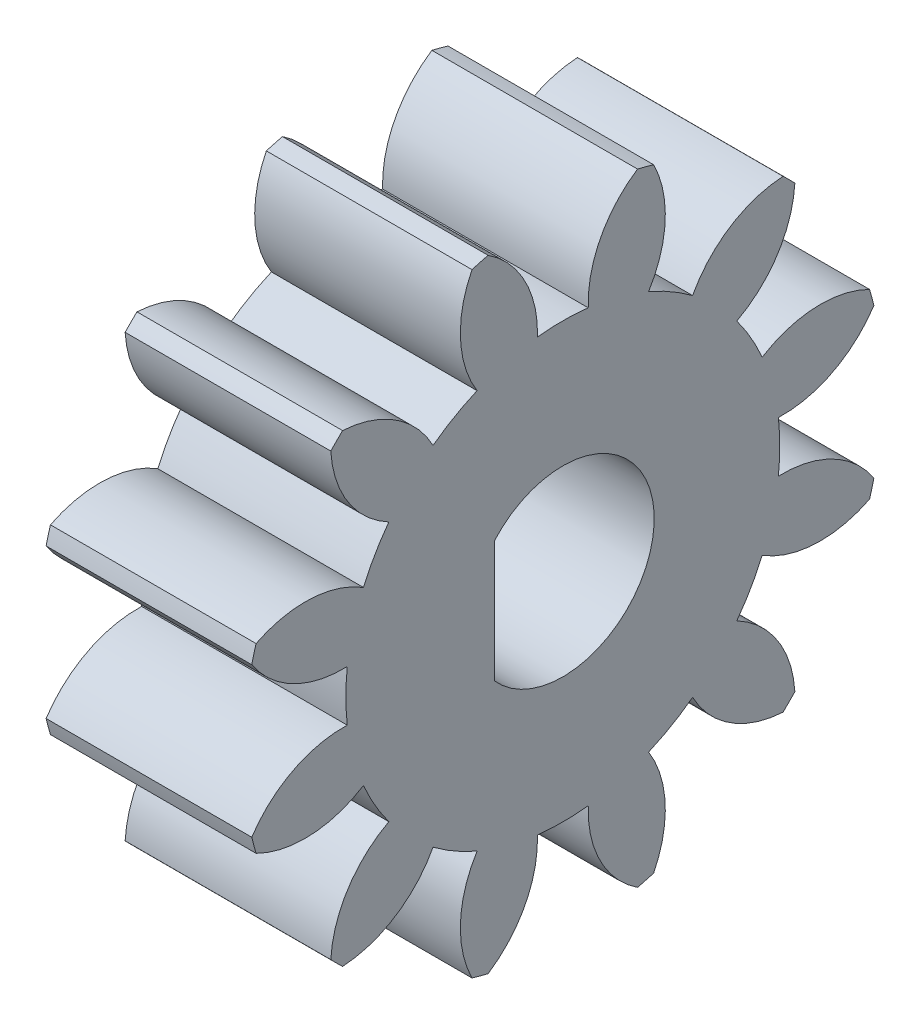
SolidWorks part; units mm, degrees
ref_plane "Plane1" through (0, 0, 0) normal (0, 0, 1) x (1, 0, 0)
ref_plane "Plane2" through (0, 0, 0) normal (0, 1, 0) x (1, 0, 0)
ref_plane "Plane3" through (0, 0, 0) normal (1, 0, 0) x (0, 0, -1)
sketch "HoldingSke" plane through (0, 0, 0) normal (0, 1, 0) x (1, 0, 0)
  line L0 (0, 0) -> (0.4891, -0.104)
  line L1 (-15, 0) -> (100, 0) construction
  line L2 (0, 0) -> (-2.1039, 2.3779)
  line L3 (0, 0) -> (-11.863, 4.5341)
  line L4 (0, 0) -> (8.4473, 1.7955)
  line L5 (0, 0) -> (-46.8476, -17.4728)
  line L6 (0, 0) -> (-7.4607, -5.0337)
  line L7 (-2.1039, 2.3779) -> (8.6586, 51.2059)
  line L8 (-76.2, 54.61) -> (-74.8, 54.61)
  line L9 (-71.009, 38.7566) -> (-53.1078, 45.2721)
  line L10 (-76.2, 71.12) -> (104.1128, 71.12)
  line L11 (0, 0) -> (-9, 0)
  line L12 (-76.2, 101.6) -> (-76.133, 101.6)
  line L13 (24.9733, 27.94) -> (52.9518, 28.4284)
  line L14 (24.9733, 27.94) -> (24.9743, 27.94)
  line L15 (24.9733, 27.94) -> (100.4006, 29.5858)
  line L16 (-63.627, -2) -> (-12.827, -2)
  circle A0 centre (0, 0) radius 4
  circle A1 centre (0, 0) radius 9.499
  circle A2 centre (0, 0) radius 37.5
  circle A3 centre (0, 0) radius 4
  dimension "MHD" = 18.998
  dimension "Hub_dia" = 75
  dimension "Bore" = 8
  dimension "MBD" = 8
  dimension "Num_teeth" = 12
  dimension "Pitch" = 0.5
  dimension "Overall_len" = 50
  dimension "Show_teeth" = 12
  dimension "Thickness" = 9
  dimension "OAL" = 50.0001
  dimension "T_dim" = 1.4
  dimension "Ap" = 20
  dimension "H" = 19.05
  dimension "Pitch_radius" = 180.3128
  dimension "Width" = 9
  dimension "Backlash" = 0.067
  dimension "Addendum_fac" = 1
  dimension "Dedendum_fac" = 1.25
  dimension "Clearance_fac" = 0.25
  dimension "Dedendum_add" = 0.001
  dimension "Module" = 2
sketch "BasProSke" plane through (0, 0, 0) normal (0, 1, 0) x (1, 0, 0)
  line L0 (-10, 0) -> (60, 0) construction
  line L1 (0, 0) -> (0, 14)
  line L2 (0, 0) -> (9, 0)
  line L3 (9, 0) -> (9, 14)
  line L4 (9, 14) -> (0, 14)
  dimension "Thickness" = 9
  dimension "Diameter" = 28
revolve "Base-Revolve" add sketch "BasProSke" angle 360 about L0
sketch "TooCutSke" plane through (0, 0, 0) normal (1, 0, 0) x (0, 0, -1)
  line L1 (0, 0) -> (0, 107) construction
  line L2 (0, 0) -> (-1.6834, 11.8813) construction
  line L3 (0, 0) -> (-6.1662, 23.0126) construction
  line L4 (-1.6834, 11.8813) -> (-3.0831, 11.5063) construction
  arc A0 (1.1119, 9.4337) -> (-1.1119, 9.4337) centre (0, 0) ccw
  arc A1 (3.2981, 13.6321) -> (-3.2981, 13.6321) centre (0, 0) ccw
  circle A2 centre (0, 0) radius 12 construction
  circle A3 centre (0, 0) radius 11.2763 construction
  arc A4 (-1.1119, 9.4337) -> (-3.2981, 13.6321) centre (-5.9089, 9.6042) ccw
  arc A5 (3.2981, 13.6321) -> (1.1119, 9.4337) centre (5.9089, 9.6042) ccw
  dimension "Root_dia" = 18.998
  dimension "Overcut_dia" = 28.0508
  dimension "Pitch_dia" = 24
  dimension "Base_dia" = 22.5526
  dimension "Flank_rad" = 4.8
  dimension "Half_ang" = 15
  dimension "Half_CT" = 1.4491
extrude "ToothCut" cut sketch "TooCutSke" along normal through all
fillet "Breaks" [suppressed] radius 0.04
fillet "RootFillets" [suppressed] radius 0.501
pattern_circular "TeethCuts" count 12 every 30 about axis through (-10, 0, 0) along (1, 0, 0) of "ToothCut", "RootFillets", "Breaks"
sketch "HubNeaOneSke" plane through (0, 0, 0) normal (-1, 0, 0) x (0, 0, 1)
  circle A0 centre (0, 0) radius 9.499
  dimension "Diameter" = 18.998
extrude "HubNearOne" [suppressed] add sketch "HubNeaOneSke" along normal blind 41.0001
sketch "HubNeaBotSke" plane through (0, 0, 0) normal (-1, 0, 0) x (0, 0, 1)
  circle A0 centre (0, 0) radius 9.499
  dimension "Diameter" = 18.998
extrude "HubNearBoth" [suppressed] add sketch "HubNeaBotSke" along normal blind 20.5
ref_plane "FarPln" through (9, 0, 0) normal (1, 0, 0) x (0, 0, -1)
sketch "HubFarSke" plane through (9, 0, 0) normal (1, 0, 0) x (0, 0, -1)
  circle A0 centre (0, 0) radius 9.499
  dimension "Diameter" = 18.998
extrude "HubFar" [suppressed] add sketch "HubFarSke" along normal blind 20.5
sketch "BorSke" plane through (0, 0, 0) normal (1, 0, 0) x (0, 0, -1)
  circle A0 centre (0, 0) radius 4
  dimension "Diameter" = 8
extrude "Bore" cut sketch "BorSke" along normal mid plane 100.0001
sketch "KeySke" plane through (0, 0, 0) normal (1, 0, 0) x (0, 0, -1)
  line L0 (-1.5, 0) -> (-1.5, 5.4)
  line L1 (-1.5, 5.4) -> (1.5, 5.4)
  line L2 (1.5, 5.4) -> (1.5, 0)
  line L3 (0, 0) -> (0, 34) construction
  line L4 (-1.5, 0) -> (1.5, 0)
  dimension "Offset" = 5.4
  dimension "Width" = 3
extrude "Keyway" [suppressed] cut sketch "KeySke" along normal mid plane 100.0001
pattern_circular "Keyway2" [suppressed] count 2 every 90 about axis through (-10, 0, 0) along (1, 0, 0)
sketch "Szkic1" plane through (0, 0, 0) normal (1, 0, 0) x (0, 0, -1)
  line L0 (4, -5.8283) -> (4, 7.2616) construction
  line L2 (-7.7998, -4.1403) -> (-7.7998, 4.4855)
  line L3 (-7.7998, -4.1403) -> (-3, -4.1403)
  line L4 (-7.7998, 4.4855) -> (-3, 4.4855)
  line L5 (-3, -4.1403) -> (-3, 4.4855)
  circle A0 centre (0, 0) radius 4 construction
  dimension "D1" = 7
extrude "Dodanie-wyciągnięcie1" add sketch "Szkic1" along normal blind 9
equation "' \"Module@HoldingSke\" = 6.35"
equation "' \"Num_teeth@HoldingSke\" = 12"
equation "' \"Ap@HoldingSke\" =  20"
equation "' \"Ap@HoldingSke\" = 20"
equation "' \"Width@HoldingSke\" = 0.5 * 25.4"
equation "' \"Hub_dia@HoldingSke\"= 1 * 25.4"
equation "' \"Hub_dia@HoldingSke\" = 1 * 25.4"
equation "' \"Overall_len@HoldingSke\" = 1.0 * 25.4"
equation "' \"Bore@HoldingSke\" = 0.75 * 25.4"
equation "' \"T_dim@HoldingSke\" = 0.1 * 25.4"
equation "' \"Width@KeySke\" = 0.25 * 25.4"
equation "' \"Show_teeth@HoldingSke\" = 13"
equation "' \"Backlash@HoldingSke\" = 0.009 * 25.4"
equation "' \"Addendum_fac@HoldingSke\" = 1.0"
equation "' \"Dedendum_fac@HoldingSke\" = 1.25"
equation "' \"Dedendum_add@HoldingSke\" = 0.00005 * 25.4"
equation "' \"Clearance_fac@HoldingSke\" = 0.25"
equation "\"Pitch@HoldingSke\" = 1 / \"Module@HoldingSke\""
equation "\"Overcut_dia@TooCutSke\" = (\"Num_teeth@HoldingSke\" + 2 * \"Addendum_fac@HoldingSke\") / \"Pitch@HoldingSke\" + 0.002 * 25.4"
equation "\"Pitch_dia@TooCutSke\" = \"Num_teeth@HoldingSke\" / \"Pitch@HoldingSke\""
equation "\"Base_dia@TooCutSke\" = \"Num_teeth@HoldingSke\" / \"Pitch@HoldingSke\" * cos((\"Ap@HoldingSke\"  * 3.14159265 / 180))"
equation "\"Root_dia@TooCutSke\" = (\"Num_teeth@HoldingSke\" + 2) / \"Pitch@HoldingSke\" - 2 * (\"Addendum_fac@HoldingSke\" + \"Dedendum_fac@HoldingSke\") / \"Pitch@HoldingSke\" - \"Dedendum_add@HoldingSke\" * 2"
equation "\"Half_ang@TooCutSke\" = 180 / \"Num_teeth@HoldingSke\""
equation "\"Half_CT@TooCutSke\" = \"Num_teeth@HoldingSke\" / \"Pitch@HoldingSke\" * sin((3.14159265 / 2 / \"Num_teeth@HoldingSke\")) / 2 - 7 * \"Backlash@HoldingSke\" / 4"
equation "\"Flank_rad@TooCutSke\" = \"Num_teeth@HoldingSke\" / \"Pitch@HoldingSke\" / 5"
equation "\"Radius@RootFillets\" = \"Clearance_fac@HoldingSke\" / \"Pitch@HoldingSke\" + \"Dedendum_add@HoldingSke\""
equation "\"Break_rad@Breaks\" = 0.02 / \"Pitch@HoldingSke\""
equation "\"Thickness@HoldingSke\" = \"Width@HoldingSke\""
equation "\"OAL@HoldingSke\" = \"Thickness@HoldingSke\""
equation "\"MHD@HoldingSke\" = (\"Num_teeth@HoldingSke\" + 2) / \"Pitch@HoldingSke\" - 2 * (\"Addendum_fac@HoldingSke\" + \"Dedendum_fac@HoldingSke\")  / \"Pitch@HoldingSke\" - \"Dedendum_add@HoldingSke\" * 2"
equation "\"MBD@HoldingSke\" = (\"Num_teeth@HoldingSke\" + 2) / \"Pitch@HoldingSke\" - 2 * (\"Addendum_fac@HoldingSke\" + \"Dedendum_fac@HoldingSke\")  / \"Pitch@HoldingSke\" - \"Dedendum_add@HoldingSke\" * 2 - 0.002 * 25.4"
equation "\"MHD@HoldingSke\" = ((sgn( \"MHD@HoldingSke\" - \"Hub_dia@HoldingSke\" )-1)*( \"MHD@HoldingSke\" - \"Hub_dia@HoldingSke\" ))/-2+ \"Hub_dia@HoldingSke\""
equation "\"MBD@HoldingSke\" = ((sgn( \"MBD@HoldingSke\" - \"Bore@HoldingSke\" )-1)*( \"MBD@HoldingSke\" - \"Bore@HoldingSke\" ))/-2+ \"Bore@HoldingSke\""
equation "\"OAL@HoldingSke\" = ((sgn( \"OAL@HoldingSke\" - \"Overall_len@HoldingSke\" )+1)*( \"OAL@HoldingSke\" - \"Overall_len@HoldingSke\" ))/2 + \"Overall_len@HoldingSke\" + 0.000002 * 25.4"
equation "\"Num_teeth@TeethCuts\" = int( \"Show_teeth@HoldingSke\" ) + 1"
equation "\"Num_teeth@TeethCuts\" = ((sgn( \"Num_teeth@TeethCuts\" - \"Num_teeth@HoldingSke\" )-1)*( \"Num_teeth@TeethCuts\" - \"Num_teeth@HoldingSke\" ))/-2+ \"Num_teeth@HoldingSke\""
equation "\"Num_teeth@TeethCuts\" = ((sgn( \"Num_teeth@TeethCuts\" - 2.0)+1)*( \"Num_teeth@TeethCuts\" - 2.0))/2 +2.0"
equation "\"Angle@TeethCuts\" = 360.0 / \"Num_teeth@HoldingSke\""
equation "\"Diameter@BasProSke\" = (\"Num_teeth@HoldingSke\" + 2 * \"Addendum_fac@HoldingSke\") / \"Pitch@HoldingSke\""
equation "\"Thickness@BasProSke\"  = \"Thickness@HoldingSke\""
equation "' \"Fillet_rad@BasProSke\" =  \"Thickness@HoldingSke\" * 0.05"
equation "' \"Fillet_rad@BasProSke\" = \"Thickness@HoldingSke\" * 0.05"
equation "\"MHD@HoldingSke\" = ((sgn( \"MHD@HoldingSke\" - \"Root_dia@TooCutSke\" )-1)*( \"MHD@HoldingSke\" - \"Root_dia@TooCutSke\" ))/-2+ \"Root_dia@TooCutSke\""
equation "\"Diameter@HubNeaOneSke\" = \"MHD@HoldingSke\""
equation "\"Length@HubNearOne\" = \"OAL@HoldingSke\" - \"Thickness@BasProSke\""
equation "\"Diameter@HubNeaBotSke\" = \"MHD@HoldingSke\""
equation "\"Length@HubNearBoth\" = ( \"OAL@HoldingSke\" - \"Thickness@BasProSke\" ) / 2.0"
equation "\"Thickness@FarPln\" = \"Thickness@BasProSke\""
equation "\"Diameter@HubFarSke\" = \"MHD@HoldingSke\""
equation "\"Length@HubFar\" = ( \"OAL@HoldingSke\" - \"Thickness@BasProSke\" ) / 2.0"
equation "\"Diameter@BorSke\" = \"MBD@HoldingSke\""
equation "\"D1@Bore\" = \"OAL@HoldingSke\" * 2.0"
equation "\"D1@Keyway\" = \"OAL@HoldingSke\" * 2.0"
equation "\"Offset@KeySke\" = \"T_dim@HoldingSke\" + \"MBD@HoldingSke\" / 2.0"
